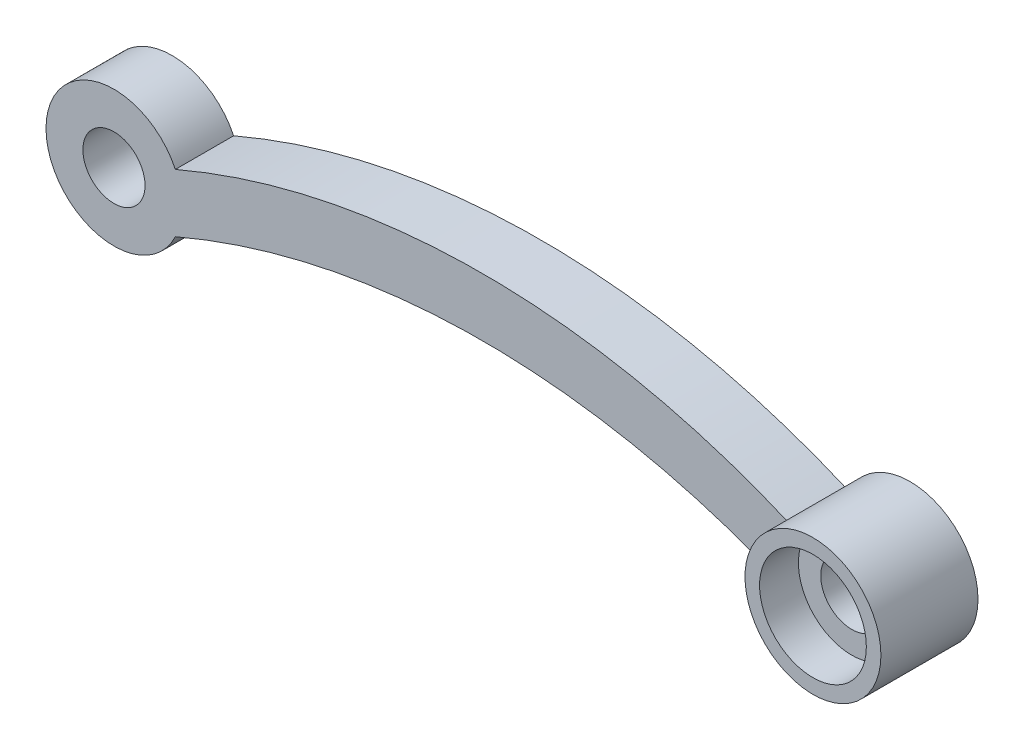
SolidWorks part; units mm, degrees
ref_plane "Front Plane" through (0, 0, 0) normal (0, 0, 1) x (1, 0, 0)
ref_plane "Top Plane" through (0, 0, 0) normal (0, 1, 0) x (1, 0, 0)
ref_plane "Right Plane" through (0, 0, 0) normal (1, 0, 0) x (0, 0, -1)
sketch "Sketch2" plane through (0, 0, 0) normal (0, 0, 1) x (1, 0, 0)
  line L0 (-19, 0) -> (-11.7639, 0) construction
  line L1 (-19, 3.5) -> (19, 3.5) construction
  line L2 (-19, -3.5) -> (19, -3.5) construction
  line L3 (0, 0) -> (0, -3.5) construction
  line L5 (15.8377, -1.5) -> (15.8377, 1.5) construction
  line L7 (-15.8377, -1.5) -> (-15.8377, 1.5) construction
  line L9 (15.8377, 1.5) -> (8.6603, 0.8202) construction
  line L10 (11.7639, 0) -> (19, 0) construction
  line L11 (-8.6603, 0.8202) -> (-15.8377, 1.5) construction
  arc A0 (-19, 3.5) -> (-19, -3.5) centre (-19, 0) ccw construction
  arc A1 (19, -3.5) -> (19, 3.5) centre (19, 0) ccw construction
  arc A2 (-15.8377, 1.5) -> (-15.8377, -1.5) centre (-19, 0) ccw
  circle A3 centre (-19, 0) radius 1.6
  circle A4 centre (19, 0) radius 1.6
  arc A5 (15.8377, 1.5) -> (15.8377, -1.5) centre (19, 0) cw
  arc A6 (-15.8377, 1.5) -> (15.8377, 1.5) centre (0, -35.231) cw
  arc A7 (-15.8377, -1.5) -> (15.8377, -1.5) centre (0, -38.231) cw
  point P2 (0, 0)
  dimension "D3" = 3.2
  dimension "D1" = 38
  dimension "D2" = 7
extrude "Boss-Extrude1" add sketch "Sketch2" along normal blind 3
sketch "Sketch3" plane through (0, 0, 3) normal (0, 0, 1) x (1, 0, 0)
  circle A0 centre (19, 0) radius 3.5
  circle A1 centre (19, 0) radius 2.75
  dimension "D1" = 7
  dimension "D2" = 5.5
extrude "Boss-Extrude2" add sketch "Sketch3" along normal blind 2
